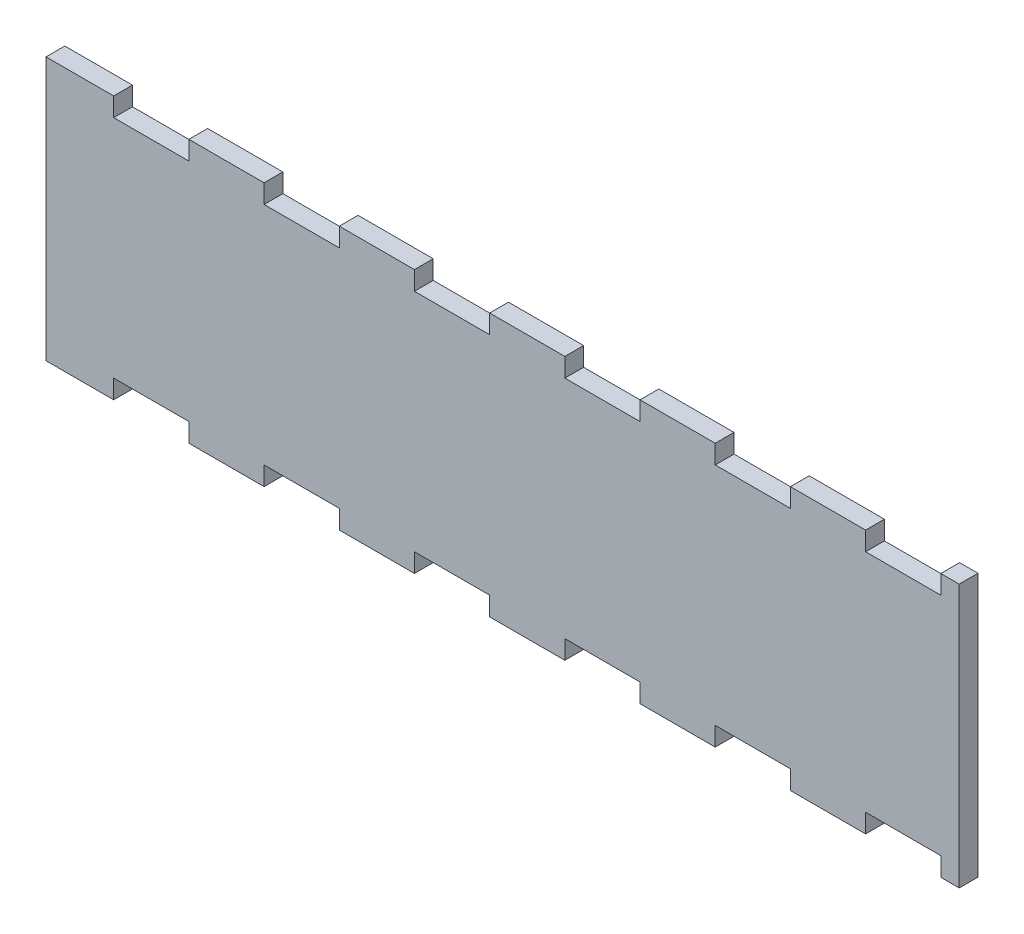
SolidWorks part; units mm, degrees
material "Acrylic (Medium-high impact)"
ref_plane "Front Plane" through (0, 0, 0) normal (0, 0, 1) x (1, 0, 0)
ref_plane "Top Plane" through (0, 0, 0) normal (0, 1, 0) x (1, 0, 0)
ref_plane "Right Plane" through (0, 0, 0) normal (1, 0, 0) x (0, 0, -1)
sketch "Sketch1" plane through (0, 0, 0) normal (0, 0, 1) x (1, 0, 0)
  line L0 (0, -22.225) -> (155.5074, -22.225) construction
  line L1 (0, 0) -> (155.5074, 0)
  line L2 (0, 0) -> (0, -44.45)
  line L3 (0, -44.45) -> (155.5074, -44.45)
  line L4 (155.5074, 0) -> (155.5074, -44.45)
  line L5 (25.4, -44.45) -> (25.4, -41.275)
  line L6 (12.7, 0) -> (25.4, 0)
  line L7 (12.7, 0) -> (12.7, -3.175)
  line L8 (12.7, -3.175) -> (25.4, -3.175)
  line L9 (25.4, 0) -> (25.4, -3.175)
  line L10 (12.7, -41.275) -> (25.4, -41.275)
  line L11 (12.7, -44.45) -> (12.7, -41.275)
  line L12 (38.1, 0) -> (38.1, -3.175)
  line L13 (38.1, -3.175) -> (50.8, -3.175)
  line L14 (50.8, 0) -> (50.8, -3.175)
  line L15 (50.8, -44.45) -> (50.8, -41.275)
  line L16 (38.1, -41.275) -> (50.8, -41.275)
  line L17 (38.1, -44.45) -> (38.1, -41.275)
  line L18 (63.5, 0) -> (63.5, -3.175)
  line L19 (63.5, -3.175) -> (76.2, -3.175)
  line L20 (76.2, 0) -> (76.2, -3.175)
  line L21 (76.2, -44.45) -> (76.2, -41.275)
  line L22 (63.5, -41.275) -> (76.2, -41.275)
  line L23 (63.5, -44.45) -> (63.5, -41.275)
  line L24 (88.9, 0) -> (88.9, -3.175)
  line L25 (88.9, -3.175) -> (101.6, -3.175)
  line L26 (101.6, 0) -> (101.6, -3.175)
  line L27 (101.6, -44.45) -> (101.6, -41.275)
  line L28 (88.9, -41.275) -> (101.6, -41.275)
  line L29 (88.9, -44.45) -> (88.9, -41.275)
  line L30 (114.3, 0) -> (114.3, -3.175)
  line L31 (114.3, -3.175) -> (127, -3.175)
  line L32 (127, 0) -> (127, -3.175)
  line L33 (127, -44.45) -> (127, -41.275)
  line L34 (114.3, -41.275) -> (127, -41.275)
  line L35 (114.3, -44.45) -> (114.3, -41.275)
  line L36 (50.8, -44.45) -> (50.8, -41.275)
  line L37 (38.1, -41.275) -> (50.8, -41.275)
  line L38 (38.1, -44.45) -> (38.1, -41.275)
  line L39 (38.1, 0) -> (38.1, -3.175)
  line L40 (38.1, -3.175) -> (50.8, -3.175)
  line L41 (50.8, 0) -> (50.8, -3.175)
  line L42 (76.2, -44.45) -> (76.2, -41.275)
  line L43 (63.5, -41.275) -> (76.2, -41.275)
  line L44 (63.5, -44.45) -> (63.5, -41.275)
  line L45 (63.5, 0) -> (63.5, -3.175)
  line L46 (63.5, -3.175) -> (76.2, -3.175)
  line L47 (76.2, 0) -> (76.2, -3.175)
  line L48 (101.6, -44.45) -> (101.6, -41.275)
  line L49 (88.9, -41.275) -> (101.6, -41.275)
  line L50 (88.9, -44.45) -> (88.9, -41.275)
  line L51 (88.9, 0) -> (88.9, -3.175)
  line L52 (88.9, -3.175) -> (101.6, -3.175)
  line L53 (101.6, 0) -> (101.6, -3.175)
  line L54 (127, -44.45) -> (127, -41.275)
  line L55 (114.3, -41.275) -> (127, -41.275)
  line L56 (114.3, -44.45) -> (114.3, -41.275)
  line L57 (114.3, 0) -> (114.3, -3.175)
  line L58 (114.3, -3.175) -> (127, -3.175)
  line L59 (127, 0) -> (127, -3.175)
  line L60 (152.4, -44.45) -> (152.4, -41.275)
  line L61 (139.7, -41.275) -> (152.4, -41.275)
  line L62 (139.7, -44.45) -> (139.7, -41.275)
  line L63 (139.7, 0) -> (139.7, -3.175)
  line L64 (139.7, -3.175) -> (152.4, -3.175)
  line L65 (152.4, 0) -> (152.4, -3.175)
  dimension "D1" = 155.5074
  dimension "D2" = 44.45
  dimension "D3" = 12.7
  dimension "D4" = 3.175
  dimension "D5" = 12.7
  dimension "D7" = 12.7
  dimension "D6" = 5
  dimension "D8" = 6
extrude "Boss-Extrude1" add sketch "Sketch1" along normal blind 3.175 contours L2 L0 L4 L1 L32 L31 L30 L26 L25 L24 L20 L19 L18 L14 L13 L12 L9 L8 L7 | L0 L2 L3 L11 L10 L5 L17 L16 L15 L23 L22 L21 L29 L28 L27 L35 L34 L33 L4
sketch "Sketch2" plane through (0, 0, 0) normal (-1, 0, 0) x (0, 0, 1)
  line L0 (0, 0) -> (3.175, 0)
  line L1 (3.175, 0) -> (3.175, -44.45)
  line L2 (3.175, -44.45) -> (0, -44.45)
  line L3 (0, -44.45) -> (0, 0)
extrude "Cut-Extrude1" cut sketch "Sketch2" against normal blind 1.27
